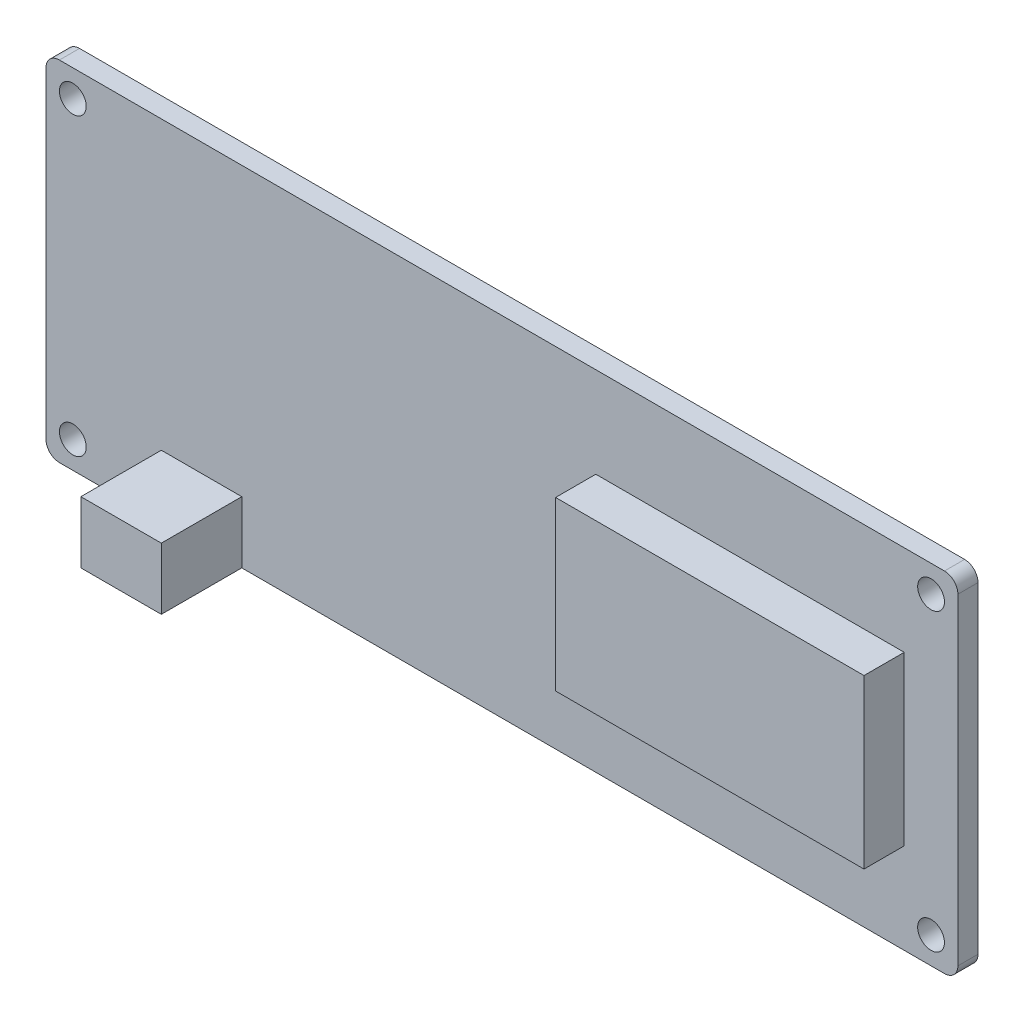
SolidWorks part; units mm, degrees
ref_plane "前基準面" through (0, 0, 0) normal (0, 0, 1) x (1, 0, 0)
ref_plane "上基準面" through (0, 0, 0) normal (0, 1, 0) x (1, 0, 0)
ref_plane "右基準面" through (0, 0, 0) normal (1, 0, 0) x (0, 0, -1)
sketch "草圖1" plane through (0, 0, 0) normal (0, 0, 1) x (1, 0, 0)
  line L0 (-44.5017, -42.6565) -> (-44.5017, -30.0565) construction
  line L1 (-33.5017, -58.0565) -> (32.4983, -58.0565)
  line L2 (-34.5017, -57.0565) -> (-34.5017, -33.0565)
  line L3 (-33.5017, -32.0565) -> (32.4983, -32.0565)
  line L4 (33.4983, -57.0565) -> (33.4983, -33.0565)
  line L5 (44.4983, -30.0565) -> (44.4983, -43.3728) construction
  line L6 (-43.5017, -29.0565) -> (43.4983, -29.0565) construction
  line L7 (-40.6, -62.6617) -> (-11.6, -62.6617) construction
  circle A0 centre (-32.5017, -34.0565) radius 1
  circle A1 centre (-32.5017, -56.0565) radius 1
  circle A2 centre (31.4983, -56.0565) radius 1
  circle A3 centre (31.4983, -34.0565) radius 1
  arc A4 (32.4983, -32.0565) -> (33.4983, -33.0565) centre (32.4983, -33.0565) cw
  arc A5 (32.4983, -58.0565) -> (33.4983, -57.0565) centre (32.4983, -57.0565) ccw
  arc A6 (-33.5017, -58.0565) -> (-34.5017, -57.0565) centre (-33.5017, -57.0565) cw
  arc A7 (-34.5017, -33.0565) -> (-33.5017, -32.0565) centre (-33.5017, -33.0565) cw
  point P6 (-44.5017, -36.3565)
  point P24 (33.4983, -32.0565)
  point P27 (33.4983, -58.0565)
  point P32 (-34.5017, -32.0565)
  dimension "D7" = 2
  dimension "D8" = 2
  dimension "D9" = 2
  dimension "D10" = 2
  dimension "D11" = 2
  dimension "D12" = 2
  dimension "D13" = 2
  dimension "D14" = 2
  dimension "D15" = 2
  dimension "D16" = 2
  dimension "D17" = 2
  dimension "D18" = 2
  dimension "D19" = 1
  dimension "D1" = 68
  dimension "D2" = 26
  dimension "D3" = 10
  dimension "D4" = 11
  dimension "D5" = 3
  dimension "D6" = 4.6051
extrude "填料-伸長1" add sketch "草圖1" along normal blind 1.5
sketch "草圖2" plane through (0, 0, 1.5) normal (0, 0, 1) x (1, 0, 0)
  line L0 (33.4983, -57.0565) -> (33.4983, -33.0565) construction
  line L1 (6.4983, -38.8065) -> (29.4983, -38.8065)
  line L2 (6.4983, -38.8065) -> (6.4983, -51.3065)
  line L3 (6.4983, -51.3065) -> (29.4983, -51.3065)
  line L4 (29.4983, -38.8065) -> (29.4983, -51.3065)
  line L5 (32.4983, -32.0565) -> (-33.5017, -32.0565) construction
  line L6 (-33.5017, -58.0565) -> (32.4983, -58.0565) construction
  dimension "D1" = 23
  dimension "D2" = 12.5
  dimension "D3" = 4
  dimension "D4" = 6.75
  dimension "D5" = 6.75
extrude "填料-伸長2" add sketch "草圖2" along normal blind 3
sketch "草圖3" plane through (0, 0, 1.5) normal (0, 0, 1) x (1, 0, 0)
  line L0 (-33.5017, -58.0565) -> (32.4983, -58.0565) construction
  line L1 (-25.9017, -53.4565) -> (-19.9017, -53.4565)
  line L2 (-25.9017, -53.4565) -> (-25.9017, -58.0565)
  line L3 (-25.9017, -58.0565) -> (-19.9017, -58.0565)
  line L4 (-19.9017, -53.4565) -> (-19.9017, -58.0565)
  line L5 (-34.5017, -33.0565) -> (-34.5017, -57.0565) construction
  dimension "D1" = 4.6
  dimension "D2" = 6
  dimension "D3" = 8.6
extrude "填料-伸長3" add sketch "草圖3" along normal blind 6
